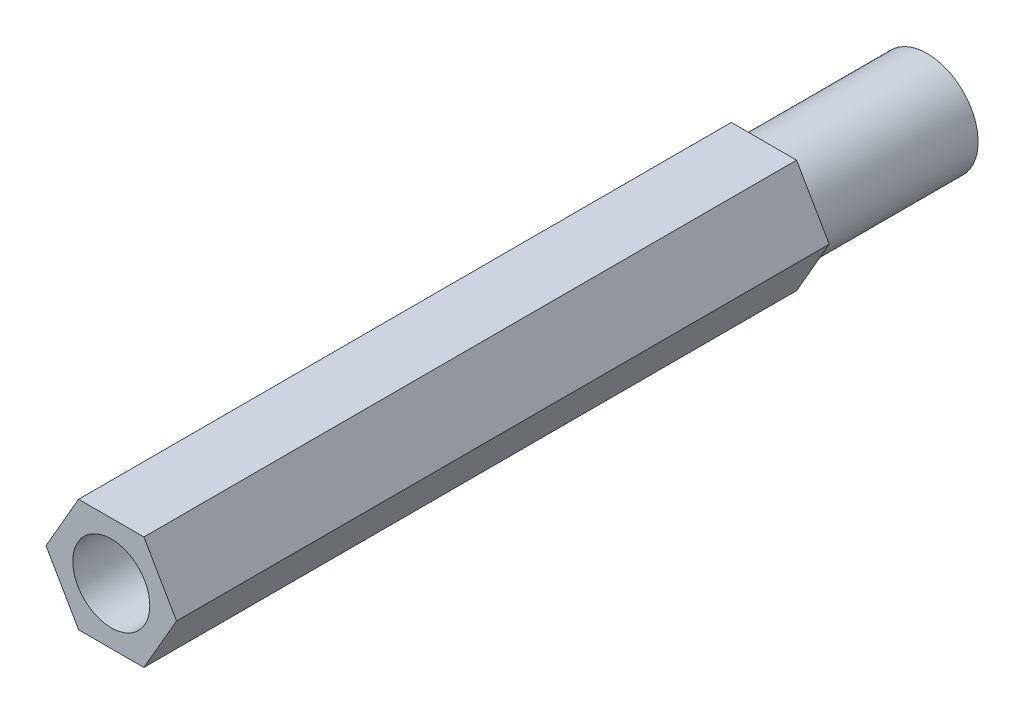
SolidWorks part; units mm, degrees
ref_plane "Front Plane" through (0, 0, 0) normal (0, 0, 1) x (1, 0, 0)
ref_plane "Top Plane" through (0, 0, 0) normal (0, 1, 0) x (1, 0, 0)
ref_plane "Right Plane" through (0, 0, 0) normal (1, 0, 0) x (0, 0, -1)
sketch "Sketch1" plane through (0, 0, 0) normal (0, 0, 1) x (1, 0, 0)
  line L1 (5.08, 0) -> (2.54, 4.3994)
  line L2 (2.54, 4.3994) -> (-2.54, 4.3994)
  line L3 (-2.54, 4.3994) -> (-5.08, 0)
  line L4 (-5.08, 0) -> (-2.54, -4.3994)
  line L5 (-2.54, -4.3994) -> (2.54, -4.3994)
  line L6 (2.54, -4.3994) -> (5.08, 0)
  circle A0 centre (0, 0) radius 4.3994 construction
  dimension "D1" = 5.08
extrude "Boss-Extrude1" add sketch "Sketch1" along normal blind 63.5
sketch "Sketch2" plane through (0, 0, 63.5) normal (0, 0, 1) x (1, 0, 0)
  circle A0 centre (0, 0) radius 2.9972
  dimension "D1" = 5.9944
extrude "Cut-Extrude1" cut sketch "Sketch2" against normal blind 12.7
sketch "Sketch3" plane through (0, 0, 0) normal (0, 0, -1) x (-1, 0, 0)
  line L0 (2.54, 4.3994) -> (5.08, 0) construction
  line L1 (5.08, 0) -> (2.54, 4.3994)
  line L2 (2.54, 4.3994) -> (-2.54, 4.3994)
  line L3 (-2.54, 4.3994) -> (-5.08, 0)
  line L4 (-5.08, 0) -> (-2.54, -4.3994)
  line L5 (-2.54, -4.3994) -> (2.54, -4.3994)
  line L6 (2.54, -4.3994) -> (5.08, 0)
  circle A0 centre (0, 0) radius 4.3994 construction
  circle A1 centre (0, 0) radius 3.9688
  dimension "D1" = 7.9375
extrude "Cut-Extrude2" cut sketch "Sketch3" against normal blind 12.7
sketch "Sketch4" plane through (-3.81, 2.1997, 0) normal (-0.866, 0.5, 0) x (0, 0, 1)
  line L0 (63.5, 2.54) -> (63.5, -2.54) construction
  line L1 (63.5, -2.54) -> (63.5, 2.54) construction
  circle A0 centre (57.15, 0) radius 1.27
  point P4 (63.5, 0)
  point P5 (63.5, 0)
  dimension "D1" = 2.54
  dimension "D2" = 6.35
extrude "Cut-Extrude3" cut sketch "Sketch4" against normal blind 5.08
